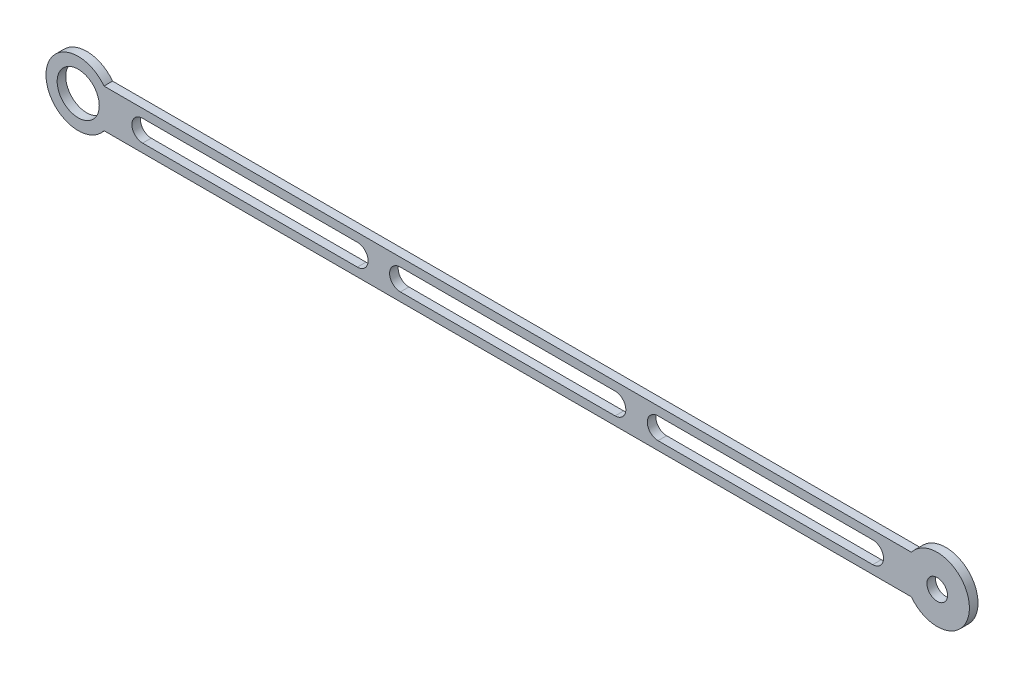
SolidWorks part; units mm, degrees
ref_plane "Front Plane" through (0, 0, 0) normal (0, 0, 1) x (1, 0, 0)
ref_plane "Top Plane" through (0, 0, 0) normal (0, 1, 0) x (1, 0, 0)
ref_plane "Right Plane" through (0, 0, 0) normal (1, 0, 0) x (0, 0, -1)
sketch "Sketch1" plane through (0, 0, 0) normal (0, 0, 1) x (1, 0, 0)
  line L0 (6, 0) -> (194, 0) construction
  line L1 (6, 4.5) -> (194, 4.5)
  line L2 (6, 4.5) -> (6, -4.5)
  line L3 (6, -4.5) -> (194, -4.5)
  line L4 (194, 4.5) -> (194, -4.5)
  line L5 (200, 0) -> (197.6, 0) construction
  line L6 (0, 0) -> (-2.3373, 0) construction
  circle A0 centre (0, 0) radius 4.9
  circle A1 centre (0, 0) radius 7.5
  circle A2 centre (200, 0) radius 2.4
  circle A3 centre (200, 0) radius 7.5
  dimension "D1" = 200
  dimension "D2" = 9.8
  dimension "D3" = 15
  dimension "D5" = 4.8
  dimension "D4" = 9
extrude "Boss-Extrude1" add sketch "Sketch1" along normal blind 2 contours A3 L1 A1 L3 | L4 A3 | L4 A3 A2 | L2 A1 L3 A0 | L3 A1 L2
sketch "Sketch2" plane through (0, 0, 2) normal (0, 0, 1) x (1, 0, 0)
  line L0 (75, 0) -> (125, 0) construction
  line L1 (75, 2.5) -> (125, 2.5)
  line L2 (75, -2.5) -> (125, -2.5)
  line L3 (135, 0) -> (185, 0) construction
  line L4 (135, 2.5) -> (185, 2.5)
  line L5 (135, -2.5) -> (185, -2.5)
  line L6 (15, 0) -> (65, 0) construction
  line L7 (15, 2.5) -> (65, 2.5)
  line L8 (15, -2.5) -> (65, -2.5)
  arc A0 (75, 2.5) -> (75, -2.5) centre (75, 0) ccw
  arc A1 (125, -2.5) -> (125, 2.5) centre (125, 0) ccw
  arc A2 (135, 2.5) -> (135, -2.5) centre (135, 0) ccw
  arc A3 (185, -2.5) -> (185, 2.5) centre (185, 0) ccw
  arc A4 (15, 2.5) -> (15, -2.5) centre (15, 0) ccw
  arc A5 (65, -2.5) -> (65, 2.5) centre (65, 0) ccw
  point P3 (100, 0)
  point P12 (160, 0)
  point P18 (40, 0)
  dimension "D1" = 50
  dimension "D2" = 100
  dimension "D3" = 5
  dimension "D4" = 2
  dimension "D5" = 2
extrude "Cut-Extrude1" cut sketch "Sketch2" against normal through all
